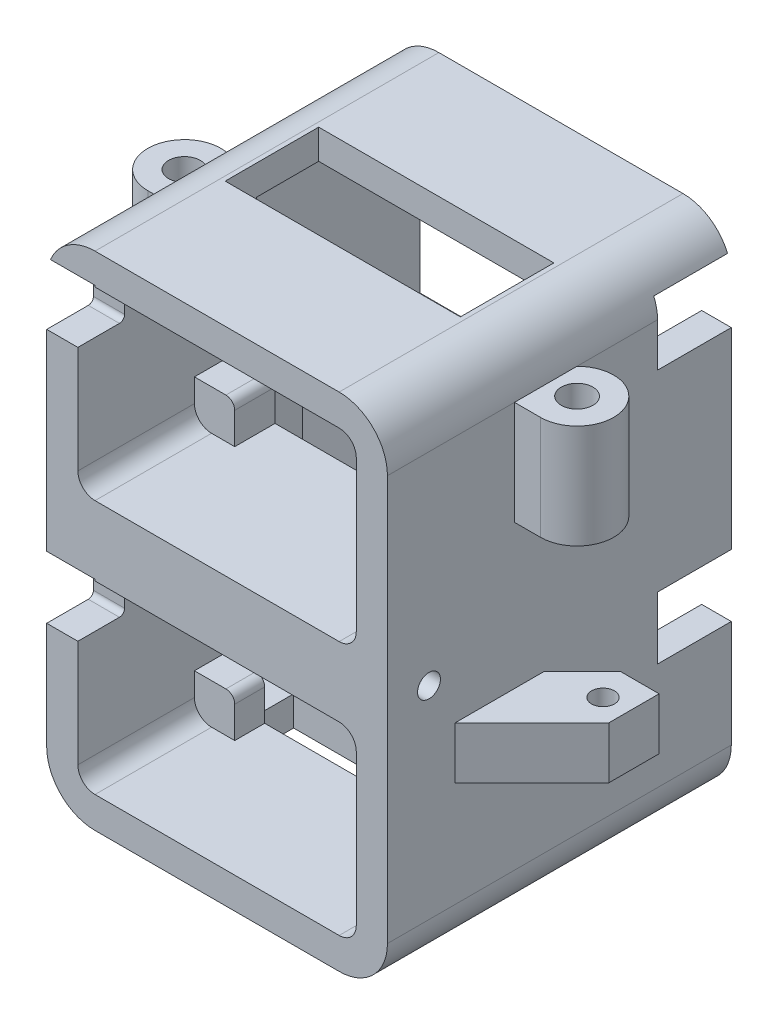
SolidWorks part; units mm, degrees
ref_plane "前视基准面" through (0, 0, 0) normal (0, 0, 1) x (1, 0, 0)
ref_plane "上视基准面" through (0, 0, 0) normal (0, 1, 0) x (1, 0, 0)
ref_plane "右视基准面" through (0, 0, 0) normal (1, 0, 0) x (0, 0, -1)
other "Configuration Table"
sketch "草图2" plane through (0, 0, 0) normal (0, 0, 1) x (1, 0, 0)
  line L20 (13.4, -7.25) -> (13.4, 7.25)
  line L21 (11.75, 8.9) -> (-16.9, 8.9)
  line L22 (-16.9, 8.9) -> (-16.9, 3.2)
  line L23 (-16.9, 3.2) -> (-13.4, 3.2)
  line L24 (-13.4, 3.2) -> (-13.4, -7.25)
  line L25 (-11.75, -8.9) -> (-3.85, -8.9)
  line L26 (-3.85, -8.9) -> (-3.85, -7.9)
  line L27 (-3.85, -7.9) -> (3.85, -7.9)
  line L28 (3.85, -7.9) -> (3.85, -8.9)
  line L29 (3.85, -8.9) -> (11.75, -8.9)
  line L40 (13.4, -7.25) -> (13.4, 7.25)
  line L41 (11.75, 8.9) -> (-16.9, 8.9)
  line L42 (-16.9, 8.9) -> (-16.9, 3.2)
  line L43 (-16.9, 3.2) -> (-13.4, 3.2)
  line L44 (-13.4, 3.2) -> (-13.4, -7.25)
  line L45 (-11.75, -8.9) -> (-3.85, -8.9)
  line L49 (3.85, -8.9) -> (11.75, -8.9)
  line L50 (-3.85, 15.6) -> (3.85, 15.6)
  line L51 (-3.85, -8.9) -> (3.85, -8.9)
  line L52 (-3.85, 12.6) -> (3.85, 12.6)
  line L53 (3.85, 12.6) -> (11.75, 12.6)
  line L54 (16.4, 17.25) -> (16.4, 31.75)
  line L55 (11.75, 36.4) -> (-19.9, 36.4)
  line L56 (-19.9, 36.4) -> (-19.9, 24.7)
  line L57 (-19.9, 24.7) -> (-16.4, 24.7)
  line L58 (-16.4, 24.7) -> (-16.4, 17.25)
  line L59 (-11.75, 12.6) -> (-3.85, 12.6)
  line L70 (13.4, 17.25) -> (13.4, 31.75)
  line L71 (11.75, 33.4) -> (-16.9, 33.4)
  line L72 (-16.9, 33.4) -> (-16.9, 27.7)
  line L73 (-16.9, 27.7) -> (-13.4, 27.7)
  line L74 (-13.4, 27.7) -> (-13.4, 17.25)
  line L75 (-11.75, 15.6) -> (-3.85, 15.6)
  line L76 (-3.85, 15.6) -> (-3.85, 16.6)
  line L77 (-3.85, 16.6) -> (3.85, 16.6)
  line L78 (3.85, 16.6) -> (3.85, 15.6)
  line L79 (3.85, 15.6) -> (11.75, 15.6)
  line L80 (13.4, 17.25) -> (13.4, 31.75)
  line L81 (11.75, 33.4) -> (-16.9, 33.4)
  line L82 (-16.9, 33.4) -> (-16.9, 27.7)
  line L83 (-16.9, 27.7) -> (-13.4, 27.7)
  line L84 (-13.4, 27.7) -> (-13.4, 17.25)
  line L85 (-11.75, 15.6) -> (-3.85, 15.6)
  line L89 (3.85, 15.6) -> (11.75, 15.6)
  line L90 (16.4, -7.25) -> (16.4, 7.25)
  line L91 (11.75, 11.9) -> (-19.9, 11.9)
  line L92 (-19.9, 11.9) -> (-19.9, 0.2)
  line L93 (-19.9, 0.2) -> (-16.4, 0.2)
  line L94 (-16.4, 0.2) -> (-16.4, -7.25)
  line L95 (-11.75, -11.9) -> (-3.85, -11.9)
  line L96 (-3.85, -11.9) -> (3.85, -11.9)
  line L97 (3.85, -11.9) -> (11.75, -11.9)
  line L98 (-16.4, 0.2) -> (-16.4, 3.2)
  line L99 (-16.4, 17.25) -> (-16.4, 11.9)
  line L100 (16.4, 17.25) -> (16.4, 7.25)
  line L101 (-16.9, 33.4) -> (-19.9, 33.4)
  line L102 (-16.9, 27.7) -> (-19.9, 27.7)
  line L103 (-16.9, 8.9) -> (-19.9, 8.9)
  line L104 (-16.4, 24.7) -> (-16.4, 27.7)
  line L105 (-16.4, 36.4) -> (-16.4, 33.4)
  line L106 (-16.4, 11.9) -> (-16.4, 8.9)
  line L107 (-16.4, 33.4) -> (-16.4, 27.7)
  line L108 (-16.4, 8.9) -> (-16.4, 3.2)
  line L109 (-13.4, 27.7) -> (-13.4, 33.4)
  line L110 (-13.4, 3.2) -> (-13.4, 8.9)
  arc A1 (-11.75, 11.9) -> (-16.4, 7.25) centre (-11.75, 7.25) ccw
  arc A2 (-11.75, 8.9) -> (-13.4, 7.25) centre (-11.75, 7.25) ccw
  arc A3 (-11.75, 8.9) -> (-13.4, 7.25) centre (-11.75, 7.25) ccw
  arc A6 (13.4, 7.25) -> (11.75, 8.9) centre (11.75, 7.25) ccw
  arc A7 (-13.4, -7.25) -> (-11.75, -8.9) centre (-11.75, -7.25) ccw
  arc A8 (11.75, -8.9) -> (13.4, -7.25) centre (11.75, -7.25) ccw
  arc A12 (13.4, 7.25) -> (11.75, 8.9) centre (11.75, 7.25) ccw
  arc A13 (-13.4, -7.25) -> (-11.75, -8.9) centre (-11.75, -7.25) ccw
  arc A14 (11.75, -8.9) -> (13.4, -7.25) centre (11.75, -7.25) ccw
  arc A15 (11.75, 12.6) -> (16.4, 17.25) centre (11.75, 17.25) ccw
  arc A16 (16.4, 31.75) -> (11.75, 36.4) centre (11.75, 31.75) ccw
  arc A17 (-16.4, 17.25) -> (-11.75, 12.6) centre (-11.75, 17.25) ccw
  arc A21 (13.4, 31.75) -> (11.75, 33.4) centre (11.75, 31.75) ccw
  arc A22 (-13.4, 17.25) -> (-11.75, 15.6) centre (-11.75, 17.25) ccw
  arc A23 (11.75, 15.6) -> (13.4, 17.25) centre (11.75, 17.25) ccw
  arc A24 (13.4, 31.75) -> (11.75, 33.4) centre (11.75, 31.75) ccw
  arc A25 (-13.4, 17.25) -> (-11.75, 15.6) centre (-11.75, 17.25) ccw
  arc A26 (11.75, 15.6) -> (13.4, 17.25) centre (11.75, 17.25) ccw
  arc A27 (16.4, 7.25) -> (11.75, 11.9) centre (11.75, 7.25) ccw
  arc A28 (-16.4, -7.25) -> (-11.75, -11.9) centre (-11.75, -7.25) ccw
  arc A29 (11.75, -11.9) -> (16.4, -7.25) centre (11.75, -7.25) ccw
  arc A31 (-11.75, 36.4) -> (-16.4, 31.75) centre (-11.75, 31.75) ccw
  arc A32 (-11.75, 33.4) -> (-13.4, 31.75) centre (-11.75, 31.75) ccw
  arc A33 (-11.75, 33.4) -> (-13.4, 31.75) centre (-11.75, 31.75) ccw
  dimension "D1" = 0.15
  dimension "D2" = 0.15
  dimension "D3" = 3
  dimension "D4" = 3
  dimension "D5" = 0.15
  dimension "D6" = 3
  dimension "D7" = 0.15
  dimension "D8" = 3
extrude "凸台-拉伸2" add sketch "草图2" against normal up to surface (11.22 mm away)
sketch "草图3" plane through (0, 0, -11.22) normal (0, 0, -1) x (-1, 0, 0)
  line L0 (11.75, -8.9) -> (-11.75, -8.9) construction
  line L2 (-11.75, 8.9) -> (11.75, 8.9) construction
  line L3 (11.75, -8.9) -> (-11.75, -8.9)
  line L4 (16.4, -7.25) -> (16.4, 31.75)
  line L5 (11.75, 36.4) -> (-11.75, 36.4)
  line L6 (-16.4, 31.75) -> (-16.4, -7.25)
  line L7 (-11.75, -11.9) -> (11.75, -11.9)
  line L12 (16.4, -7.25) -> (16.4, 31.75)
  line L13 (11.75, 36.4) -> (-11.75, 36.4)
  line L14 (-16.4, 31.75) -> (-16.4, -7.25)
  line L16 (-11.75, -11.9) -> (11.75, -11.9)
  line L20 (-13.4, -7.25) -> (-13.4, 7.25)
  line L21 (-11.75, 33.4) -> (11.75, 33.4) construction
  line L22 (-13.4, 17.25) -> (-13.4, 31.75) construction
  line L23 (-9.52, -8.6) -> (-9.52, -5.87)
  line L24 (-10.37, -5.02) -> (-13.1, -5.02)
  line L25 (-13.1, -5.02) -> (-13.1, -7.25)
  line L26 (-11.75, -8.6) -> (-9.52, -8.6)
  line L27 (-9.52, -8.6) -> (-9.52, -5.87)
  line L28 (-10.37, -5.02) -> (-13.1, -5.02)
  line L32 (11.75, 15.6) -> (-11.75, 15.6) construction
  line L33 (-11.75, 33.4) -> (11.75, 33.4)
  line L34 (-13.4, 17.25) -> (-13.4, 31.75)
  line L36 (11.75, 15.6) -> (-11.75, 15.6)
  line L38 (13.4, 7.25) -> (13.4, -7.25) construction
  line L39 (13.1, -5.02) -> (10.37, -5.02)
  line L40 (9.52, -5.87) -> (9.52, -8.6)
  line L41 (9.52, -8.6) -> (11.75, -8.6)
  line L42 (13.1, -7.25) -> (13.1, -5.02)
  line L43 (13.1, -5.02) -> (10.37, -5.02)
  line L44 (9.52, -5.87) -> (9.52, -8.6)
  line L47 (13.4, 7.25) -> (13.4, -7.25)
  line L48 (-11.75, 8.9) -> (11.75, 8.9) construction
  line L49 (-9.52, 15.75) -> (-9.52, 18.63)
  line L50 (-10.37, 19.48) -> (-13.25, 19.48)
  line L51 (-13.1, 6.82) -> (-11.67, 6.82)
  line L52 (-11.32, 7.17) -> (-11.32, 8.6)
  line L53 (-11.32, 8.6) -> (-11.75, 8.6)
  line L54 (-13.1, 7.25) -> (-13.1, 6.82)
  line L55 (-13.1, 6.82) -> (-11.67, 6.82)
  line L56 (-11.32, 7.17) -> (-11.32, 8.6)
  line L59 (-13.1, 6.82) -> (-13.4, 6.82)
  line L60 (-13.4, -7.25) -> (-13.4, 7.25) construction
  line L61 (-9.52, 15.6) -> (-9.52, 18.63)
  line L62 (-10.37, 19.48) -> (-13.4, 19.48)
  line L63 (11.32, 8.6) -> (11.32, 7.17)
  line L64 (11.67, 6.82) -> (13.1, 6.82)
  line L65 (13.1, 6.82) -> (13.1, 7.25)
  line L66 (11.75, 8.6) -> (11.32, 8.6)
  line L67 (11.32, 8.9) -> (11.32, 7.17)
  line L68 (11.67, 6.82) -> (13.4, 6.82)
  line L71 (-11.75, 8.9) -> (11.75, 8.9)
  line L73 (-13.25, 31.32) -> (-11.67, 31.32)
  line L74 (-11.32, 31.67) -> (-11.32, 33.25)
  line L75 (-13.25, 31.32) -> (-11.67, 31.32)
  line L76 (-11.32, 31.67) -> (-11.32, 33.25)
  line L79 (11.67, 31.32) -> (13.25, 31.32)
  line L80 (11.32, 33.25) -> (11.32, 31.67)
  line L81 (11.67, 31.32) -> (13.4, 31.32)
  line L82 (11.32, 33.25) -> (11.32, 31.67)
  line L83 (-13.25, 31.32) -> (-13.4, 31.32)
  line L84 (-11.32, 33.25) -> (-11.32, 33.4)
  line L85 (9.52, 18.63) -> (9.52, 15.75)
  line L86 (13.25, 19.48) -> (10.37, 19.48)
  line L87 (9.52, 18.63) -> (9.52, 15.6)
  line L88 (13.4, 19.48) -> (10.37, 19.48)
  line L89 (11.32, 33.25) -> (11.32, 33.4)
  line L90 (-11.32, 8.6) -> (-11.32, 8.9)
  line L91 (13.4, 31.75) -> (13.4, 17.25) construction
  line L92 (13.4, 31.75) -> (13.4, 17.25)
  line L93 (-13.1, -5.02) -> (-13.4, -5.02)
  line L94 (-9.52, -8.6) -> (-9.52, -8.9)
  line L95 (9.52, -8.6) -> (9.52, -8.9)
  line L96 (13.1, -5.02) -> (13.4, -5.02)
  arc A0 (-13.4, -7.25) -> (-11.75, -8.9) centre (-11.75, -7.25) ccw construction
  arc A1 (11.75, -8.9) -> (13.4, -7.25) centre (11.75, -7.25) ccw construction
  arc A2 (-11.75, 8.9) -> (-13.4, 7.25) centre (-11.75, 7.25) ccw construction
  arc A3 (11.75, -11.9) -> (16.4, -7.25) centre (11.75, -7.25) ccw
  arc A4 (-11.75, 36.4) -> (-16.4, 31.75) centre (-11.75, 31.75) ccw
  arc A5 (-16.4, -7.25) -> (-11.75, -11.9) centre (-11.75, -7.25) ccw
  arc A6 (11.75, -11.9) -> (16.4, -7.25) centre (11.75, -7.25) ccw
  arc A9 (-11.75, 36.4) -> (-16.4, 31.75) centre (-11.75, 31.75) ccw
  arc A10 (-9.52, -5.87) -> (-10.37, -5.02) centre (-10.37, -5.87) ccw
  arc A11 (-13.1, -7.25) -> (-11.75, -8.6) centre (-11.75, -7.25) ccw
  arc A12 (-9.52, -5.87) -> (-10.37, -5.02) centre (-10.37, -5.87) ccw
  arc A14 (-16.4, -7.25) -> (-11.75, -11.9) centre (-11.75, -7.25) ccw
  arc A15 (-13.4, -7.25) -> (-11.75, -8.9) centre (-11.75, -7.25) ccw
  arc A16 (11.75, -8.9) -> (13.4, -7.25) centre (11.75, -7.25) ccw
  arc A17 (-11.75, 8.9) -> (-13.4, 7.25) centre (-11.75, 7.25) ccw
  arc A18 (10.37, -5.02) -> (9.52, -5.87) centre (10.37, -5.87) ccw
  arc A19 (11.75, -8.6) -> (13.1, -7.25) centre (11.75, -7.25) ccw
  arc A20 (10.37, -5.02) -> (9.52, -5.87) centre (10.37, -5.87) ccw
  arc A22 (-11.75, 33.4) -> (-13.4, 31.75) centre (-11.75, 31.75) ccw construction
  arc A23 (11.75, 15.6) -> (13.4, 17.25) centre (11.75, 17.25) ccw construction
  arc A24 (-11.67, 6.82) -> (-11.32, 7.17) centre (-11.67, 7.17) ccw
  arc A25 (-11.75, 8.6) -> (-13.1, 7.25) centre (-11.75, 7.25) ccw
  arc A26 (-11.67, 6.82) -> (-11.32, 7.17) centre (-11.67, 7.17) ccw
  arc A28 (-13.4, 17.25) -> (-11.75, 15.6) centre (-11.75, 17.25) ccw construction
  arc A29 (-11.75, 33.4) -> (-13.4, 31.75) centre (-11.75, 31.75) ccw
  arc A30 (11.32, 7.17) -> (11.67, 6.82) centre (11.67, 7.17) ccw
  arc A31 (13.1, 7.25) -> (11.75, 8.6) centre (11.75, 7.25) ccw
  arc A32 (11.32, 7.17) -> (11.67, 6.82) centre (11.67, 7.17) ccw
  arc A34 (11.75, 15.6) -> (13.4, 17.25) centre (11.75, 17.25) ccw
  arc A35 (-13.4, 17.25) -> (-11.75, 15.6) centre (-11.75, 17.25) ccw
  arc A36 (13.4, 7.25) -> (11.75, 8.9) centre (11.75, 7.25) ccw construction
  arc A37 (13.4, 7.25) -> (11.75, 8.9) centre (11.75, 7.25) ccw
  arc A38 (-9.52, 18.63) -> (-10.37, 19.48) centre (-10.37, 18.63) ccw
  arc A39 (-9.52, 18.63) -> (-10.37, 19.48) centre (-10.37, 18.63) ccw
  arc A41 (-11.67, 31.32) -> (-11.32, 31.67) centre (-11.67, 31.67) ccw
  arc A42 (-11.67, 31.32) -> (-11.32, 31.67) centre (-11.67, 31.67) ccw
  arc A44 (11.32, 31.67) -> (11.67, 31.32) centre (11.67, 31.67) ccw
  arc A45 (11.32, 31.67) -> (11.67, 31.32) centre (11.67, 31.67) ccw
  arc A46 (13.4, 31.75) -> (11.75, 33.4) centre (11.75, 31.75) ccw construction
  arc A47 (10.37, 19.48) -> (9.52, 18.63) centre (10.37, 18.63) ccw
  arc A48 (10.37, 19.48) -> (9.52, 18.63) centre (10.37, 18.63) ccw
  arc A49 (13.4, 31.75) -> (11.75, 33.4) centre (11.75, 31.75) ccw
  arc A52 (16.4, 31.75) -> (11.75, 36.4) centre (11.75, 31.75) ccw
  arc A53 (16.4, 31.75) -> (11.75, 36.4) centre (11.75, 31.75) ccw
  dimension "D1" = 0.15
  dimension "D2" = 0.15
  dimension "D3" = 0.15
  dimension "D4" = 0.15
  dimension "D5" = 0
  dimension "D6" = 0.15
  dimension "D7" = 0.15
  dimension "D8" = 0.15
  dimension "D9" = 0.15
extrude "凸台-拉伸3" add sketch "草图3" along normal up to surface (3.88 mm away)
sketch "草图4" plane through (-16.4, 0, 0) normal (-1, 0, 0) x (0, 0, 1)
  line L8 (0.3, 9.05) -> (-4, 9.05)
  line L9 (-4.5, 8.55) -> (-4.5, 3.55)
  line L10 (-4, 3.05) -> (0.3, 3.05)
  line L11 (0.3, 3.05) -> (0.3, 9.05)
  line L12 (0.3, 9.05) -> (-4, 9.05)
  line L13 (-4.5, 8.55) -> (-4.5, 3.55)
  line L14 (-4, 3.05) -> (0.3, 3.05)
  line L15 (0.3, 3.05) -> (0.3, 9.05)
  line L20 (0.3, 33.55) -> (-4, 33.55)
  line L21 (-4.5, 33.05) -> (-4.5, 28.05)
  line L22 (-4, 27.55) -> (0.3, 27.55)
  line L23 (0.3, 27.55) -> (0.3, 33.55)
  line L24 (0.3, 33.55) -> (-4, 33.55)
  line L25 (-4.5, 33.05) -> (-4.5, 28.05)
  line L26 (-4, 27.55) -> (0.3, 27.55)
  line L27 (0.3, 27.55) -> (0.3, 33.55)
  arc A4 (-4, 9.05) -> (-4.5, 8.55) centre (-4, 8.55) ccw
  arc A5 (-4.5, 3.55) -> (-4, 3.05) centre (-4, 3.55) ccw
  arc A6 (-4, 9.05) -> (-4.5, 8.55) centre (-4, 8.55) ccw
  arc A7 (-4.5, 3.55) -> (-4, 3.05) centre (-4, 3.55) ccw
  arc A10 (-4, 33.55) -> (-4.5, 33.05) centre (-4, 33.05) ccw
  arc A11 (-4.5, 28.05) -> (-4, 27.55) centre (-4, 28.05) ccw
  arc A12 (-4, 33.55) -> (-4.5, 33.05) centre (-4, 33.05) ccw
  arc A13 (-4.5, 28.05) -> (-4, 27.55) centre (-4, 28.05) ccw
  dimension "D1" = 0.3
  dimension "D2" = 0.3
extrude "切除-拉伸1" cut sketch "草图4" against normal blind 4.65
ref_plane "基准面1" through (0, 31.75, 0) normal (0, 1, 0) x (1, 0, 0)
sketch "草图8" plane through (0, 31.75, 0) normal (0, 1, 0) x (1, 0, 0)
  line L0 (18.9, 12.23) -> (15.375, 12.23)
  line L1 (15.375, 12.23) -> (15.375, 15.755)
  line L2 (16.4, 15.1) -> (16.4, 0) construction
  line L3 (-12.113, 15.755) -> (18.9, 15.755) construction
  line L4 (9.73, 15.91) -> (-9.73, 15.91) construction
  line L5 (-9.73, 15.6) -> (9.73, 15.6) construction
  circle A2 centre (18.9, 15.755) radius 1.525
  circle A3 centre (18.9, 15.755) radius 3.525
  dimension "D1" = 3.05
  dimension "D3" = 2.5
  dimension "D2" = 2
extrude "凸台-拉伸5" add sketch "草图8" against normal blind 10 contours A3 A2 | A3 L1 L0
mirror "镜向1" about plane through (0, 0, 0) normal (1, 0, 0) of "凸台-拉伸5"
sketch "草图9" plane through (0, 0, -15.1) normal (0, 0, -1) x (-1, 0, 0)
  line L0 (-11.32, 33.4) -> (11.32, 33.4) construction
  line L1 (-11.32, 33.4) -> (11.32, 33.4)
  line L2 (-11.32, 33.4) -> (-11.32, 36.4)
  line L3 (-11.32, 36.4) -> (11.32, 36.4)
  line L4 (11.32, 33.4) -> (11.32, 36.4)
  line L5 (11.75, 36.4) -> (-11.75, 36.4) construction
  line L6 (-11.32, 31.67) -> (-11.32, 33.4) construction
  line L7 (11.32, 33.4) -> (11.32, 31.67) construction
extrude "切除-拉伸3" cut sketch "草图9" against normal blind 3
sketch "草图10" plane through (0, 0, -15.1) normal (0, 0, -1) x (-1, 0, 0)
  line L0 (-11.75, -11.9) -> (11.75, -11.9) construction
  line L1 (-10.73, -11.9) -> (10.73, -11.9)
  line L2 (-10.73, -11.9) -> (-10.73, -5.02)
  line L3 (-10.73, -5.02) -> (10.73, -5.02)
  line L4 (10.73, -11.9) -> (10.73, -5.02)
  line L5 (13.4, -5.02) -> (10.37, -5.02) construction
  line L6 (-9.73, 46.85) -> (-9.73, 45.95) construction
  line L7 (9.73, 94.6) -> (9.73, -23.1) construction
  dimension "D1" = 1
  dimension "D2" = 1
extrude "切除-拉伸4" cut sketch "草图10" against normal blind 1
sketch "草图11" plane through (0, 2.8903, 0) normal (0, 1, 0) x (1, 0, 0)
  line L0 (19.0958, 16.405) -> (19.0958, 15.105)
  line L1 (16.4, 15.1) -> (16.4, 0) construction
  line L2 (16.4, 15.1) -> (16.4, 0)
  line L3 (16.4, 15.1) -> (19.0958, 15.1)
  line L4 (19.0958, 9.855) -> (16.4, 9.855)
  line L5 (16.4, 15.1) -> (19.0958, 17.7958)
  line L6 (19.0958, 17.7958) -> (20.055, 18.755)
  line L7 (19.0958, 21.655) -> (19.0958, 16.405)
  line L8 (19.0958, 16.405) -> (20.6358, 16.405)
  line L9 (20.6358, 15.105) -> (19.0958, 15.105)
  line L10 (19.0958, 15.105) -> (19.0958, 9.855)
  line L11 (19.0958, 9.855) -> (23.7958, 9.855)
  line L12 (23.7958, 9.855) -> (23.7958, 21.655)
  line L13 (23.7958, 21.655) -> (19.0958, 21.655)
  line L14 (19.0958, 17.7958) -> (19.0958, 16.405)
  line L17 (19.0958, 15.105) -> (19.0958, 9.855)
  line L18 (19.0958, 9.855) -> (23.7958, 9.855)
  line L19 (23.7958, 9.855) -> (23.7958, 18.755)
  line L21 (20.055, 18.755) -> (23.7958, 18.755)
  line L22 (23.7958, 13.9124) -> (16.4, 6.5166)
  circle A0 centre (21.3958, 15.755) radius 1.1
  arc A1 (20.6358, 15.105) -> (20.6358, 16.405) centre (21.3958, 15.755) ccw
  dimension "D6" = 2.2
  dimension "D2" = 45
  dimension "D3" = 3
  dimension "D4" = 5.245
  dimension "D5" = 45
  dimension "D7" = 3
  dimension "D1" = 0
extrude "凸台-拉伸6" add sketch "草图11" along normal blind 5
sketch "草图12" plane through (-16.4, 0, 0) normal (-1, 0, 0) x (0, 0, 1)
  circle A0 centre (-4, 12.25) radius 1.1
  dimension "D1" = 2.2
extrude "切除-拉伸5" cut sketch "草图12" against normal blind 8
sketch "草图13" plane through (16.4, 0, 0) normal (1, 0, 0) x (0, 0, -1)
  circle A0 centre (4, 12.25) radius 1.1
  dimension "D1" = 2.2
extrude "切除-拉伸6" cut sketch "草图13" against normal blind 8
sketch "草图14" plane through (0, 0, -15.1) normal (0, 0, -1) x (-1, 0, 0)
  line L0 (-9.52, 18.63) -> (-16.4, 18.63)
  line L1 (-10.37, 19.48) -> (-13.4, 19.48) construction
  line L2 (-16.4, 9.05) -> (16.4, 9.05)
  line L3 (-9.52, 18.63) -> (16.4, 18.63)
  line L4 (-11.32, 8.9) -> (11.32, 8.9) construction
  line L6 (9.88, -23.25) -> (9.88, 94.6704)
  line L7 (-9.88, -23.25) -> (9.88, -23.25)
  line L8 (-9.88, 94.6704) -> (-9.88, -23.25)
  line L9 (9.88, -23.25) -> (9.88, 94.6704)
  line L10 (-9.88, -23.25) -> (9.88, -23.25)
  line L11 (-9.88, 94.6704) -> (-9.88, -23.25)
  line L19 (16.4, 3.05) -> (13.4, 3.05)
  line L20 (16.4, -7.25) -> (16.4, 3.05)
  line L21 (-11.75, -11.9) -> (11.75, -11.9)
  line L22 (-16.4, 31.75) -> (-16.4, -7.25)
  line L23 (11.75, 36.4) -> (-11.75, 36.4)
  line L24 (11.75, 33.55) -> (16.0375, 33.55)
  line L25 (11.75, 33.4) -> (11.75, 33.55)
  line L26 (-11.75, 33.4) -> (11.75, 33.4)
  line L27 (-13.4, 17.25) -> (-13.4, 31.75)
  line L28 (11.75, 15.6) -> (-11.75, 15.6)
  line L29 (13.4, 27.55) -> (13.4, 17.25)
  line L30 (16.4, 27.55) -> (13.4, 27.55)
  line L31 (16.4, 9.05) -> (16.4, 27.55)
  line L32 (11.75, 9.05) -> (16.4, 9.05)
  line L33 (11.75, 8.9) -> (11.75, 9.05)
  line L34 (-11.75, 8.9) -> (11.75, 8.9)
  line L35 (-13.4, -7.25) -> (-13.4, 7.25)
  line L36 (11.75, -8.9) -> (-11.75, -8.9)
  line L37 (13.4, 3.05) -> (13.4, -7.25)
  line L39 (16.4, -7.25) -> (16.4, 9.05)
  line L40 (-11.75, -11.9) -> (11.75, -11.9)
  line L41 (-16.4, 31.75) -> (-16.4, -7.25)
  line L42 (11.75, 36.4) -> (-11.75, 36.4)
  line L50 (16.4, 9.05) -> (16.4, 31.75)
  arc A2 (9.88, 94.6704) -> (-9.88, 94.6704) centre (0, 82.8253) ccw
  arc A3 (9.88, 94.6704) -> (-9.88, 94.6704) centre (0, 82.8253) ccw
  arc A10 (11.75, -11.9) -> (16.4, -7.25) centre (11.75, -7.25) ccw
  arc A11 (-16.4, -7.25) -> (-11.75, -11.9) centre (-11.75, -7.25) ccw
  arc A12 (-11.75, 36.4) -> (-16.4, 31.75) centre (-11.75, 31.75) ccw
  arc A13 (16.0375, 33.55) -> (11.75, 36.4) centre (11.75, 31.75) ccw
  arc A14 (-11.75, 33.4) -> (-13.4, 31.75) centre (-11.75, 31.75) ccw
  arc A15 (-13.4, 17.25) -> (-11.75, 15.6) centre (-11.75, 17.25) ccw
  arc A16 (11.75, 15.6) -> (13.4, 17.25) centre (11.75, 17.25) ccw
  arc A17 (-11.75, 8.9) -> (-13.4, 7.25) centre (-11.75, 7.25) ccw
  arc A18 (-13.4, -7.25) -> (-11.75, -8.9) centre (-11.75, -7.25) ccw
  arc A19 (11.75, -8.9) -> (13.4, -7.25) centre (11.75, -7.25) ccw
  arc A20 (11.75, -11.9) -> (16.4, -7.25) centre (11.75, -7.25) ccw
  arc A21 (-16.4, -7.25) -> (-11.75, -11.9) centre (-11.75, -7.25) ccw
  arc A22 (-11.75, 36.4) -> (-16.4, 31.75) centre (-11.75, 31.75) ccw
  arc A23 (16.4, 31.75) -> (11.75, 36.4) centre (11.75, 31.75) ccw
  line M49 (16.4, -7.25) -> (16.4, 21.75)
  line M75 (-16.4, 21.75) -> (-16.4, 7.8903)
  dimension "D2" = 0.15
  dimension "D4" = 0.15
  dimension "D3" = 0.85
extrude "凸台-拉伸7" add sketch "草图14" along normal blind 3 contours L11 L0 L2 M75 | L9 L2 L3 M49
sketch "草图15" plane through (0, 0, -15.1) normal (0, 0, -1) x (-1, 0, 0)
  line L0 (-9.52, -8.9) -> (9.52, -8.9) construction
  line L5 (16.4, 9.05) -> (16.4, 18.63) construction
  line L9 (-16.4, 18.63) -> (-16.4, 9.05) construction
  line L13 (16.4, 9.05) -> (16.4, 18.63)
  line L17 (-16.4, 18.63) -> (-16.4, 9.05)
  line L24 (-11.75, 36.4) -> (11.75, 36.4)
  line L25 (-16.4, 21.75) -> (-16.4, 18.63) construction
  line L26 (-16.4, 21.75) -> (-16.4, 18.63)
  line L27 (-16.4, 2.8903) -> (-16.4, -7.25) construction
  line L28 (-16.4, 2.8903) -> (-16.4, -7.25)
  line L29 (-16.4, 21.75) -> (-16.4, 31.75)
  line L30 (-16.4, 9.05) -> (-16.4, 2.8903)
  line L31 (-11.75, -11.9) -> (11.75, -11.9)
  line L32 (-11.32, 33.4) -> (11.32, 33.4) construction
  line L33 (-13.55, 33.55) -> (13.55, 33.55)
  line L34 (-13.55, 33.55) -> (-13.55, -9.05)
  line L35 (-13.55, -9.05) -> (13.55, -9.05)
  line L36 (13.55, 33.55) -> (13.55, -9.05)
  line L37 (-13.4, 19.48) -> (-13.4, 31.32) construction
  line L39 (13.4, 31.32) -> (13.4, 19.48) construction
  line L40 (16.4, -7.25) -> (16.4, 9.05)
  line L41 (16.4, 18.63) -> (16.4, 31.75)
  line L44 (-16.4, 15.5) -> (-16.4, 9)
  line L46 (16.4, 15.5) -> (16.4, 9)
  arc A0 (16.4, 31.75) -> (11.75, 36.4) centre (11.75, 31.75) ccw construction
  arc A1 (-11.75, 36.4) -> (-16.4, 31.75) centre (-11.75, 31.75) ccw construction
  arc A2 (16.4, 31.75) -> (11.75, 36.4) centre (11.75, 31.75) ccw
  arc A3 (-11.75, 36.4) -> (-16.4, 31.75) centre (-11.75, 31.75) ccw
  arc A4 (-16.4, -7.25) -> (-11.75, -11.9) centre (-11.75, -7.25) ccw construction
  arc A5 (-16.4, -7.25) -> (-11.75, -11.9) centre (-11.75, -7.25) ccw
  arc A6 (11.75, -11.9) -> (16.4, -7.25) centre (11.75, -7.25) ccw construction
  arc A7 (11.75, -11.9) -> (16.4, -7.25) centre (11.75, -7.25) ccw
  point P2 (0, 0)
  point P24 (-16.4, 14.7976)
  dimension "D1" = 0.15
  dimension "D2" = 0.15
  dimension "D4" = 0.15
  dimension "D3" = 0.15
extrude "凸台-拉伸8" add sketch "草图15" along normal blind 18
sketch "草图16" plane through (0, 0, -18.1) normal (0, 0, -1) x (-1, 0, 0)
  line L0 (-13.55, 33.55) -> (-13.55, -9.05) construction
  line L1 (-13.55, 9.05) -> (13.55, 9.05)
  line L2 (-13.55, 9.05) -> (-13.55, 15.45)
  line L3 (-13.55, 15.45) -> (13.55, 15.45)
  line L4 (13.55, 9.05) -> (13.55, 15.45)
  line L5 (13.55, 33.55) -> (13.55, -9.05) construction
  line L6 (-11.32, 8.9) -> (11.32, 8.9) construction
  line L7 (9.52, 15.6) -> (-9.52, 15.6) construction
  dimension "D1" = 0.15
  dimension "D2" = 0.15
extrude "凸台-拉伸9" add sketch "草图16" along normal up to surface (15 mm away)
sketch "草图17" plane through (0, 9.05, 0) normal (0, -1, 0) x (1, 0, 0)
  line L0 (-9.88, -18.1) -> (0, -27.98)
  line L1 (0, -27.98) -> (9.88, -18.1)
  line L2 (9.88, -18.1) -> (-9.88, -18.1) construction
  line L3 (-9.88, -18.1) -> (9.88, -18.1)
  dimension "D1" = 45
  dimension "D2" = 45
extrude "切除-拉伸8" cut sketch "草图17" against normal up to next
sketch "草图18" plane through (13.55, 0, 0) normal (-1, 0, 0) x (0, 0, 1)
  line L0 (0, -7.25) -> (0, 31.75) construction
  line L1 (-33.1, 3.05) -> (-26, 3.05)
  line L2 (-33.1, 3.05) -> (-33.1, 9.05)
  line L3 (-33.1, 9.05) -> (-26, 9.05)
  line L4 (-26, 3.05) -> (-26, 9.05)
  line L5 (-33.1, 27.55) -> (-26, 27.55)
  line L6 (-33.1, 27.55) -> (-33.1, 33.55)
  line L7 (-33.1, 33.55) -> (-26, 33.55)
  line L8 (-26, 27.55) -> (-26, 33.55)
  point P4 (-30.1, 33.55)
  point P9 (-30.1, 9.05)
  point P10 (0, 0)
  dimension "D2" = 6
  dimension "D3" = 6
  dimension "D5" = 26
extrude "切除-拉伸9" cut sketch "草图18" against normal up to next
sketch "草图19" plane through (0, -11.9, 0) normal (0, -1, 0) x (1, 0, 0)
  line L1 (-10.73, -14.1) -> (10.73, -14.1)
  line L2 (-10.73, -14.1) -> (-10.73, -15.1)
  line L3 (-10.73, -15.1) -> (10.73, -15.1)
  line L4 (10.73, -14.1) -> (10.73, -15.1)
  line L5 (-10.73, -15.1) -> (10.73, -15.1)
  line L6 (-10.73, -15.1) -> (-10.73, -18.1)
  line L7 (-10.73, -18.1) -> (10.73, -18.1)
  line L8 (10.73, -15.1) -> (10.73, -18.1)
  line M10 (10.73, -14.1) -> (10.73, -15.1)
  line M11 (10.73, -15.1) -> (-10.73, -15.1)
  line M12 (-10.73, -15.1) -> (-10.73, -14.1)
  line M13 (-10.73, -14.1) -> (10.73, -14.1)
  dimension "D1" = 3
extrude "切除-拉伸10" cut sketch "草图19" against normal up to next contours M10 M13 M12 M11 | L8 L6 L7 M11
sketch "草图20" plane through (0, 36.4, 0) normal (0, 1, 0) x (1, 0, 0)
  line L1 (-11.32, 15.1) -> (11.32, 15.1)
  line L2 (-11.32, 15.1) -> (-11.32, 21.1)
  line L3 (-11.32, 21.1) -> (11.32, 21.1)
  line L4 (11.32, 15.1) -> (11.32, 21.1)
  point P5 (11.32, 15.1)
  dimension "D1" = 6
extrude "切除-拉伸11" cut sketch "草图20" against normal up to next
equation "\"top_residual_len\"= 0.15"
equation "\"D2@草图15\"=\"top_residual_len\""
equation "\"D4@草图15\"=\"top_residual_len\""
equation "\"D1@草图15\"=\"top_residual_len\""
equation "\"D3@草图15\"=\"top_residual_len\""
equation "\"D2@草图16\"=\"top_residual_len\""
equation "\"D1@草图16\"=\"top_residual_len\""
equation "\"D4@草图14\"=\"top_residual_len\""
